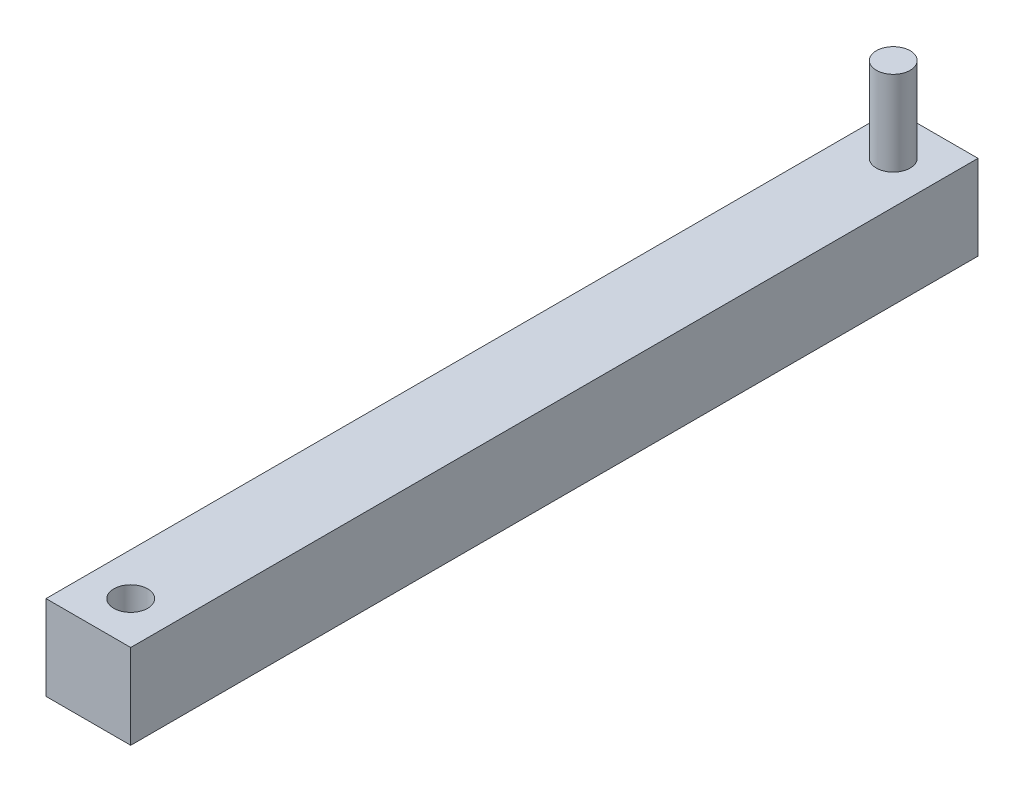
SolidWorks part; units mm, degrees
material "Cast Alloy Steel"
ref_plane "Front Plane" through (0, 0, 0) normal (0, 0, 1) x (1, 0, 0)
ref_plane "Top Plane" through (0, 0, 0) normal (0, 1, 0) x (1, 0, 0)
ref_plane "Right Plane" through (0, 0, 0) normal (1, 0, 0) x (0, 0, -1)
sketch "Sketch2" plane through (0, 0, 0) normal (0, 0, 1) x (1, 0, 0)
  line L1 (-5, 5) -> (5, 5)
  line L2 (-5, 5) -> (-5, -5)
  line L3 (-5, -5) -> (5, -5)
  line L4 (5, 5) -> (5, -5)
  line L5 (-5, 5) -> (5, -5) construction
  line L6 (-5, -5) -> (5, 5) construction
  point P0 (0, 0)
  dimension "D1" = 10
  dimension "D2" = 10
extrude "Boss-Extrude1" add sketch "Sketch2" along normal blind 100
sketch "Sketch3" plane through (0, 5, 0) normal (0, 1, 0) x (1, 0, 0)
  line L0 (5, -100) -> (-5, -100) construction
  line L1 (-5, -100) -> (-5, 0) construction
  circle A0 centre (0, -95) radius 2
  dimension "D1" = 4
  dimension "D2" = 5
  dimension "D3" = 5
extrude "Cut-Extrude1" cut sketch "Sketch3" against normal up to next
sketch "Sketch4" plane through (0, 5, 0) normal (0, 1, 0) x (1, 0, 0)
  line L0 (5, 0) -> (-5, 0) construction
  line L1 (-5, -100) -> (-5, 0) construction
  circle A0 centre (0, -5) radius 2
  dimension "D1" = 4
  dimension "D2" = 5
  dimension "D3" = 5
extrude "Boss-Extrude2" add sketch "Sketch4" along normal blind 10
